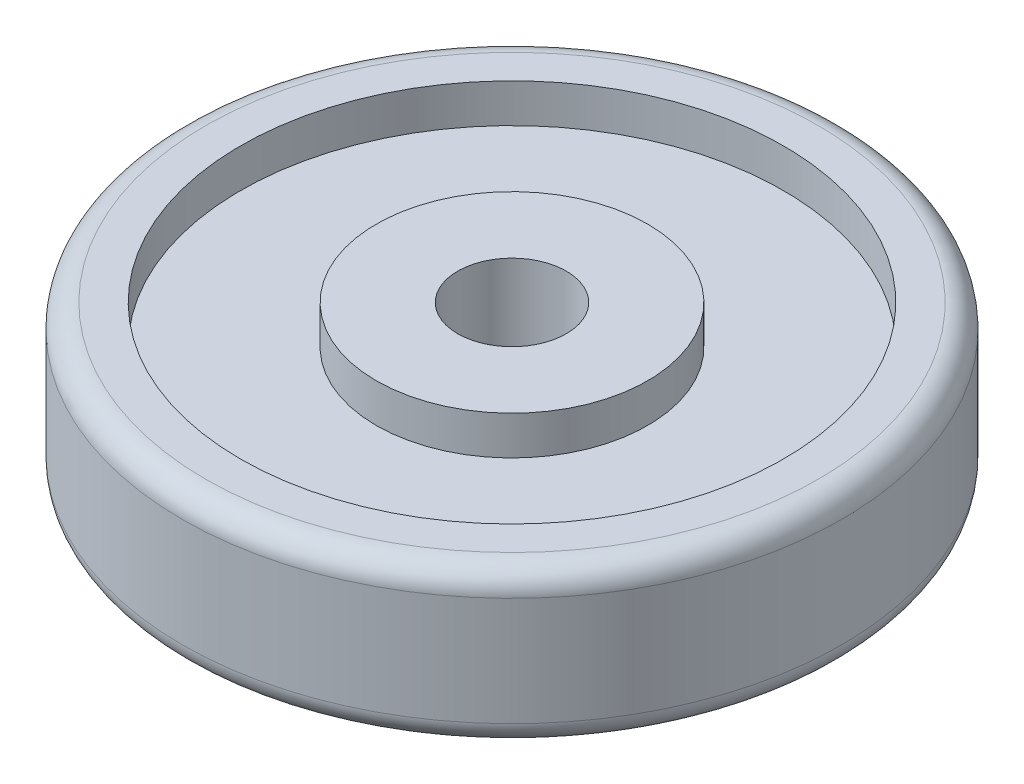
SolidWorks part; units mm, degrees
ref_plane "前视基准面" through (0, 0, 0) normal (0, 0, 1) x (1, 0, 0)
ref_plane "上视基准面" through (0, 0, 0) normal (0, 1, 0) x (1, 0, 0)
ref_plane "右视基准面" through (0, 0, 0) normal (1, 0, 0) x (0, 0, -1)
sketch "草图1" plane through (0, 0, 0) normal (0, 1, 0) x (1, 0, 0)
  circle A0 centre (0, 0) radius 42.5
  circle A1 centre (0, 0) radius 7
  dimension "D1" = 85
  dimension "D2" = 14
extrude "凸台-拉伸1" add sketch "草图1" along normal blind 20
sketch "草图2" plane through (0, 20, 0) normal (0, 1, 0) x (1, 0, 0)
  circle A0 centre (0, 0) radius 35
  circle A1 centre (0, 0) radius 17.5
  dimension "D1" = 70
  dimension "D2" = 35
extrude "切除-拉伸1" cut sketch "草图2" against normal blind 5
sketch "草图3" plane through (0, 0, 0) normal (0, -1, 0) x (1, 0, 0)
  circle A0 centre (0, 0) radius 35
  circle A1 centre (0, 0) radius 17.5
  dimension "D1" = 70
  dimension "D2" = 35
extrude "切除-拉伸2" cut sketch "草图3" against normal blind 5
fillet "圆角1" radius 3 2 edges at (0, 0, 42.5) (0, 20, 42.5)
